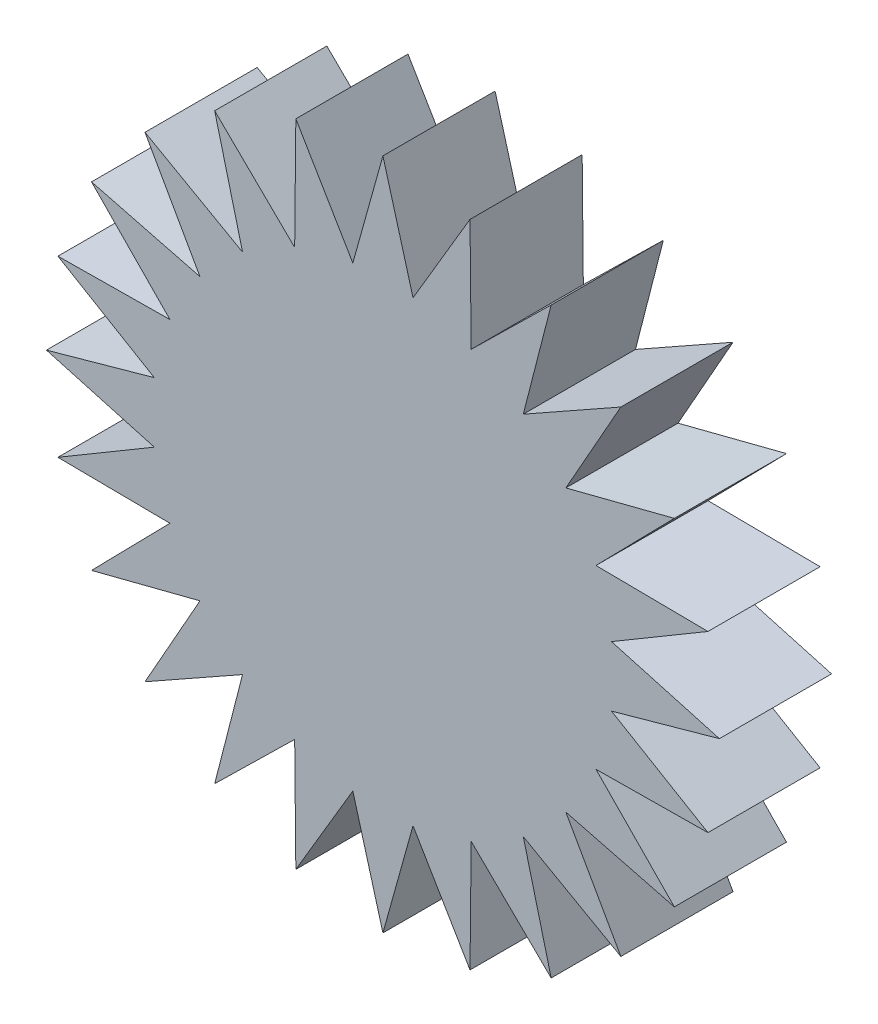
SolidWorks part; units mm, degrees
ref_plane "Plan de face" through (0, 0, 0) normal (0, 0, 1) x (1, 0, 0)
ref_plane "Plan de dessus" through (0, 0, 0) normal (0, 1, 0) x (1, 0, 0)
ref_plane "Plan de droite" through (0, 0, 0) normal (1, 0, 0) x (0, 0, -1)
sketch "Esquisse1" plane through (0, 0, 0) normal (0, 0, 1) x (1, 0, 0)
  circle A0 centre (0, 0) radius 15
  dimension "D1" = 30
extrude "Boss.-Extru.1" add sketch "Esquisse1" along normal blind 5
sketch "Esquisse2" plane through (0, 0, 5) normal (0, 0, 1) x (1, 0, 0)
  line L0 (0, 15) -> (0, 8.2053) construction
  line L1 (0, 15) -> (-1.4233, 9.8982)
  line L2 (0, 15) -> (1.4233, 9.8982)
  line L3 (3.8823, 14.4889) -> (1.187, 9.9293)
  line L4 (3.8823, 14.4889) -> (3.9367, 9.1925)
  line L5 (7.5, 12.9904) -> (3.7165, 9.2837)
  line L6 (7.5, 12.9904) -> (6.1817, 7.8604)
  line L7 (10.6066, 10.6066) -> (5.9926, 8.0055)
  line L8 (10.6066, 10.6066) -> (8.0055, 5.9926)
  line L9 (12.9904, 7.5) -> (7.8604, 6.1817)
  line L10 (12.9904, 7.5) -> (9.2837, 3.7165)
  line L11 (14.4889, 3.8823) -> (9.1925, 3.9367)
  line L12 (14.4889, 3.8823) -> (9.9293, 1.187)
  line L13 (15, 0) -> (9.8982, 1.4233)
  line L14 (15, 0) -> (9.8982, -1.4233)
  line L15 (14.4889, -3.8823) -> (9.9293, -1.187)
  line L16 (14.4889, -3.8823) -> (9.1925, -3.9367)
  line L17 (12.9904, -7.5) -> (9.2837, -3.7165)
  line L18 (12.9904, -7.5) -> (7.8604, -6.1817)
  line L19 (10.6066, -10.6066) -> (8.0055, -5.9926)
  line L20 (10.6066, -10.6066) -> (5.9926, -8.0055)
  line L21 (7.5, -12.9904) -> (6.1817, -7.8604)
  line L22 (7.5, -12.9904) -> (3.7165, -9.2837)
  line L23 (3.8823, -14.4889) -> (3.9367, -9.1925)
  line L24 (3.8823, -14.4889) -> (1.187, -9.9293)
  line L25 (0, -15) -> (1.4233, -9.8982)
  line L26 (0, -15) -> (-1.4233, -9.8982)
  line L27 (-3.8823, -14.4889) -> (-1.187, -9.9293)
  line L28 (-3.8823, -14.4889) -> (-3.9367, -9.1925)
  line L29 (-7.5, -12.9904) -> (-3.7165, -9.2837)
  line L30 (-7.5, -12.9904) -> (-6.1817, -7.8604)
  line L31 (-10.6066, -10.6066) -> (-5.9926, -8.0055)
  line L32 (-10.6066, -10.6066) -> (-8.0055, -5.9926)
  line L33 (-12.9904, -7.5) -> (-7.8604, -6.1817)
  line L34 (-12.9904, -7.5) -> (-9.2837, -3.7165)
  line L35 (-14.4889, -3.8823) -> (-9.1925, -3.9367)
  line L36 (-14.4889, -3.8823) -> (-9.9293, -1.187)
  line L37 (-15, 0) -> (-9.8982, -1.4233)
  line L38 (-15, 0) -> (-9.8982, 1.4233)
  line L39 (-14.4889, 3.8823) -> (-9.9293, 1.187)
  line L40 (-14.4889, 3.8823) -> (-9.1925, 3.9367)
  line L41 (-12.9904, 7.5) -> (-9.2837, 3.7165)
  line L42 (-12.9904, 7.5) -> (-7.8604, 6.1817)
  line L43 (-10.6066, 10.6066) -> (-8.0055, 5.9926)
  line L44 (-10.6066, 10.6066) -> (-5.9926, 8.0055)
  line L45 (-7.5, 12.9904) -> (-6.1817, 7.8604)
  line L46 (-7.5, 12.9904) -> (-3.7165, 9.2837)
  line L47 (-3.8823, 14.4889) -> (-3.9367, 9.1925)
  line L48 (-3.8823, 14.4889) -> (-1.187, 9.9293)
  circle A0 centre (0, 0) radius 10
  circle A1 centre (0, 0) radius 15 construction
  point P81 (0, 0)
  circle M4 centre (0, 0) radius 15
  dimension "D1" = 20
  dimension "D2" = 5
  dimension "D3" = 5.1018
  dimension "D4" = 24
extrude "Enlèv. mat.-Extru.1" cut sketch "Esquisse2" against normal blind 5 contours L45 L44 M4 | L47 L46 M4 | L48 L1 M4 | L3 L2 M4 | L5 L4 M4 | L7 L6 M4 | L9 L8 M4 | L11 L10 M4 | L13 L12 M4 | L15 L14 M4 | L17 L16 M4 | L19 L18 M4 | L21 L20 M4 | L23 L22 M4 | L25 L24 M4 | L27 L26 M4 | L29 L28 M4 | L31 L30 M4 | L33 L32 M4 | L35 L34 M4 | L37 L36 M4 | L39 L38 M4 | L41 L40 M4 | L43 L42 M4
